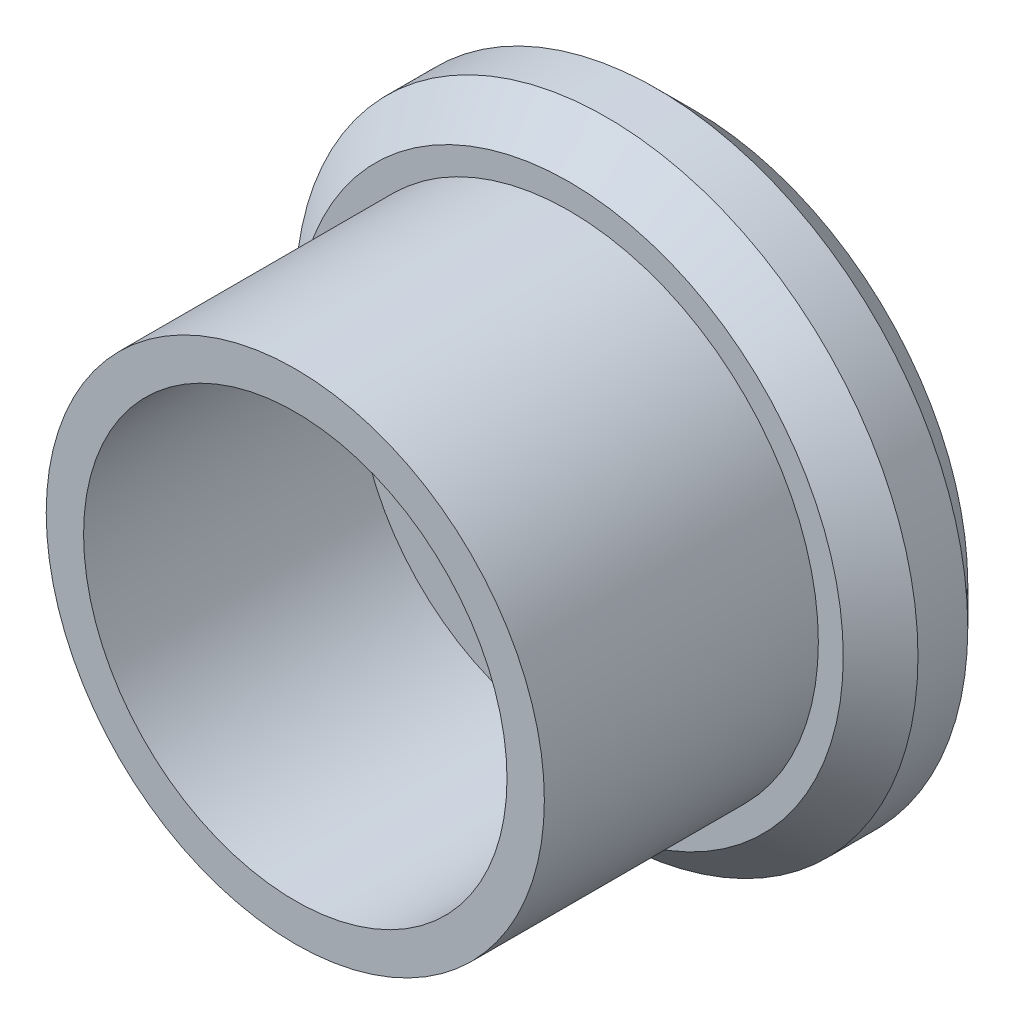
SolidWorks part; units mm, degrees
ref_plane "前视" through (0, 0, 0) normal (0, 0, 1) x (1, 0, 0)
ref_plane "上视" through (0, 0, 0) normal (0, 1, 0) x (1, 0, 0)
ref_plane "右视" through (0, 0, 0) normal (1, 0, 0) x (0, 0, -1)
sketch "草图1" plane through (0, 0, 0) normal (0, 0, 1) x (1, 0, 0)
  circle A0 centre (0, 0) radius 17
  circle A1 centre (0, 0) radius 20
extrude "凸台-拉伸1" add sketch "草图1" along normal blind 22
cosmetic thread "装饰螺纹线1" parameters "D1"=20, "D2"=102
sketch "草图2" plane through (0, 0, 0) normal (0, 0, -1) x (-1, 0, 0)
  circle A0 centre (0, 0) radius 25
extrude "凸台-拉伸2" add sketch "草图2" along normal blind 10
chamfer "倒角1" distance 3 angle 45 2 edges at (-25, 0, -10) (-25, 0, 0)
